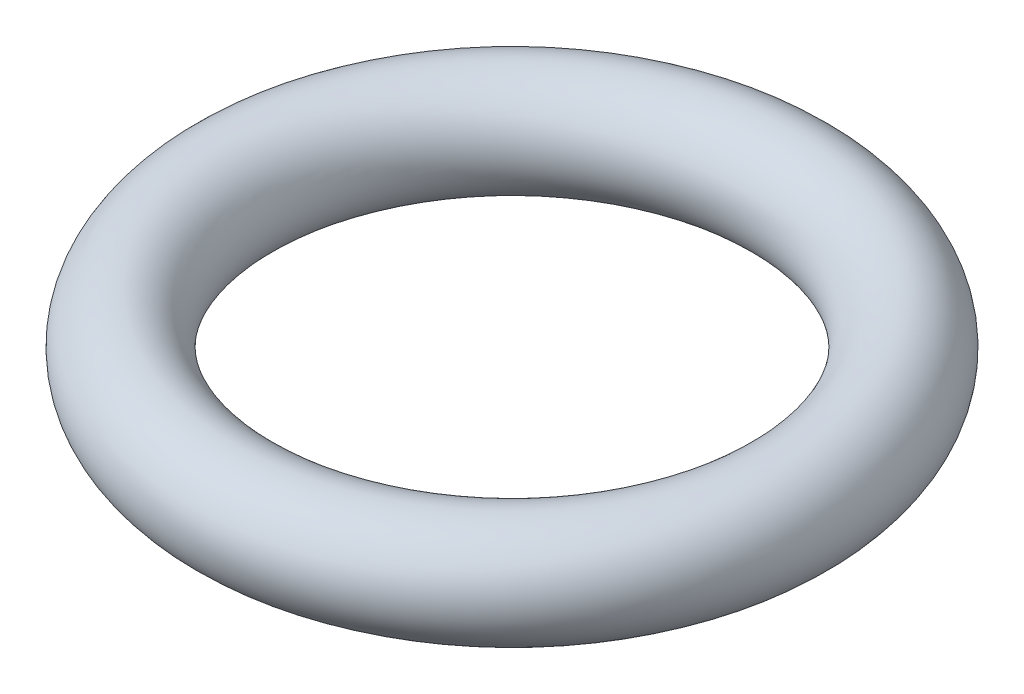
SolidWorks part; units mm, degrees
material "VITON"
ref_plane "Front Plane" through (0, 0, 0) normal (0, 0, 1) x (1, 0, 0)
ref_plane "Top Plane" through (0, 0, 0) normal (0, 1, 0) x (1, 0, 0)
ref_plane "Right Plane" through (0, 0, 0) normal (1, 0, 0) x (0, 0, -1)
sketch "Sketch1" plane through (0, 0, 0) normal (0, 0, 1) x (1, 0, 0)
  line L0 (0, 2) -> (0, -2) construction
  circle A0 centre (5.25, 0) radius 1
  dimension "D1" = 2
  dimension "D2" = 5.25
  dimension "D3" = 4
revolve "Revolve1" add sketch "Sketch1" angle 360 about L0
